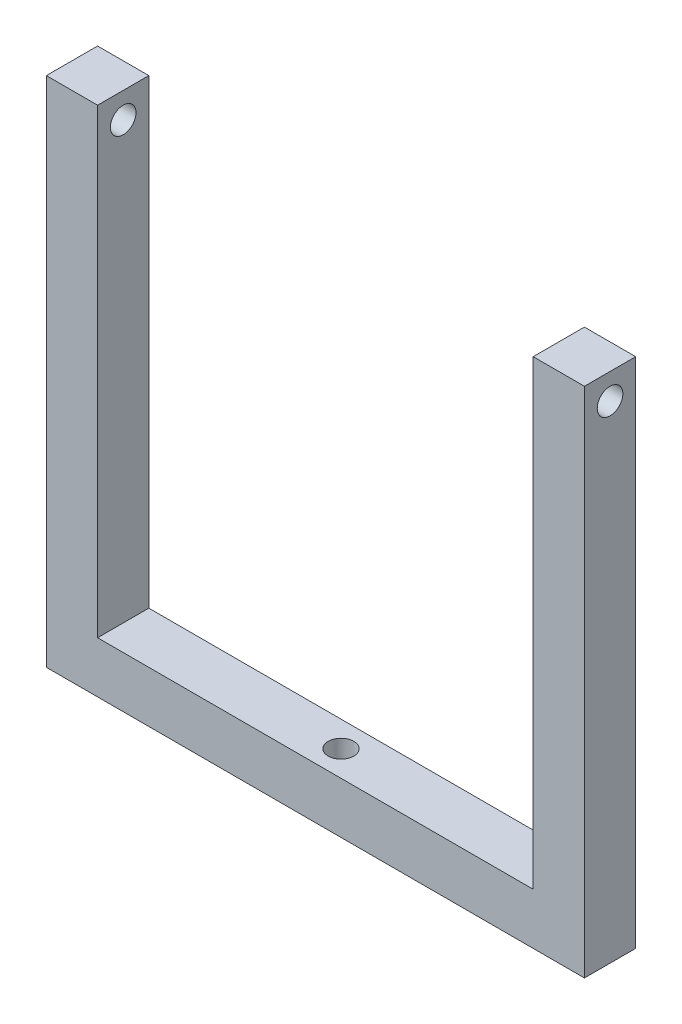
SolidWorks part; units mm, degrees
ref_plane "Front Plane" through (0, 0, 0) normal (0, 0, 1) x (1, 0, 0)
ref_plane "Top Plane" through (0, 0, 0) normal (0, 1, 0) x (1, 0, 0)
ref_plane "Right Plane" through (0, 0, 0) normal (1, 0, 0) x (0, 0, -1)
sketch "Sketch1" plane through (0, 0, 0) normal (0, 0, 1) x (1, 0, 0)
  line L0 (0, 0) -> (-12.7, 0)
  line L1 (-12.7, 0) -> (-12.7, -127)
  line L2 (-12.7, -127) -> (120.65, -127)
  line L3 (120.65, -127) -> (120.65, 0)
  line L4 (120.65, 0) -> (107.95, 0)
  line L5 (107.95, 0) -> (107.95, -114.3)
  line L6 (107.95, -114.3) -> (0, -114.3)
  line L7 (0, -114.3) -> (0, 0)
  dimension "D1" = 127
  dimension "D2" = 133.35
  dimension "D3" = 12.7
  dimension "D4" = 12.7
  dimension "D5" = 12.7
extrude "Boss-Extrude1" add sketch "Sketch1" along normal blind 12.7 contours L1 L2 L3 L4 L5 L6 L7 L0
sketch "Sketch2" plane through (-12.7, 0, 0) normal (-1, 0, 0) x (0, 0, 1)
  line L0 (0, 0) -> (0, -127) construction
  line L1 (12.7, 0) -> (0, 0) construction
  circle A0 centre (6.35, -6.35) radius 3.175
  dimension "D1" = 6.35
  dimension "D2" = 6.35
extrude "Cut-Extrude1" cut sketch "Sketch2" against normal up to surface (133.35 mm away) up to face at (120.65, -63.5, 6.35)
sketch "Sketch3" plane through (0, -114.3, 0) normal (0, 1, 0) x (1, 0, 0)
  line L0 (107.95, 0) -> (0, 0) construction
  line L1 (0, -12.7) -> (0, 0) construction
  circle A0 centre (53.975, -6.35) radius 3.175
  dimension "D1" = 6.35
  dimension "D3" = 6.35
  dimension "D2" = 53.975
extrude "Cut-Extrude2" cut sketch "Sketch3" against normal up to surface (12.7 mm away) contours A0 up to face at (53.975, -127, 6.35)
